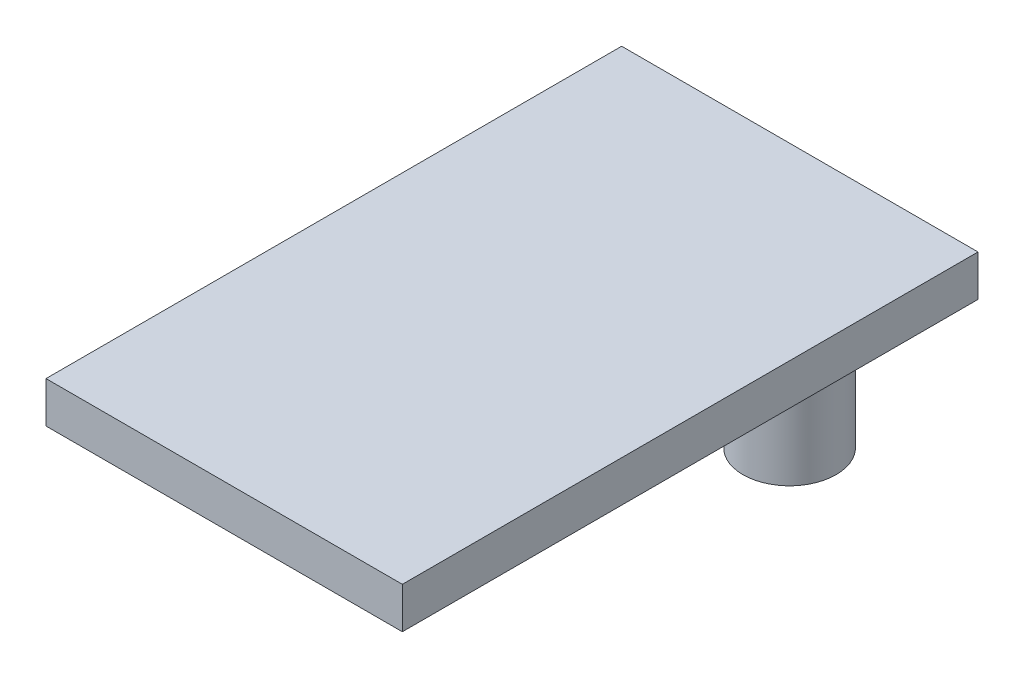
SolidWorks part; units mm, degrees
ref_plane "Front Plane" through (0, 0, 0) normal (0, 0, 1) x (1, 0, 0)
ref_plane "Top Plane" through (0, 0, 0) normal (0, 1, 0) x (1, 0, 0)
ref_plane "Right Plane" through (0, 0, 0) normal (1, 0, 0) x (0, 0, -1)
sketch "Sketch1" plane through (0, 0, 0) normal (0, 1, 0) x (1, 0, 0)
  line L1 (9.4247, -24.8343) -> (-16.5753, -24.8343)
  line L2 (9.4247, -24.8343) -> (9.4247, 17.1657)
  line L3 (9.4247, 17.1657) -> (-16.5753, 17.1657)
  line L4 (-16.5753, -24.8343) -> (-16.5753, 17.1657)
  point P0 (0, 0)
  dimension "D1" = 26
  dimension "D2" = 42
extrude "Boss-Extrude1" add sketch "Sketch1" along normal blind 3
sketch "Sketch4" plane through (0, 0, 0) normal (0, -1, 0) x (1, 0, 0)
  circle A0 centre (2.9247, -9.9157) radius 1.9
  circle A1 centre (-6.8253, 7.8343) radius 1.9
  circle A2 centre (-6.8253, 7.8343) radius 3.4
  circle A3 centre (2.9247, -9.9157) radius 3.4
  point P8 (-6.8253, 7.8343)
  point P10 (2.9492, -9.9881)
  point P11 (2.9247, -9.9157)
  dimension "D1" = 1.5
  dimension "D2" = 1.5
extrude "Boss-Extrude2" add sketch "Sketch4" along normal blind 9
